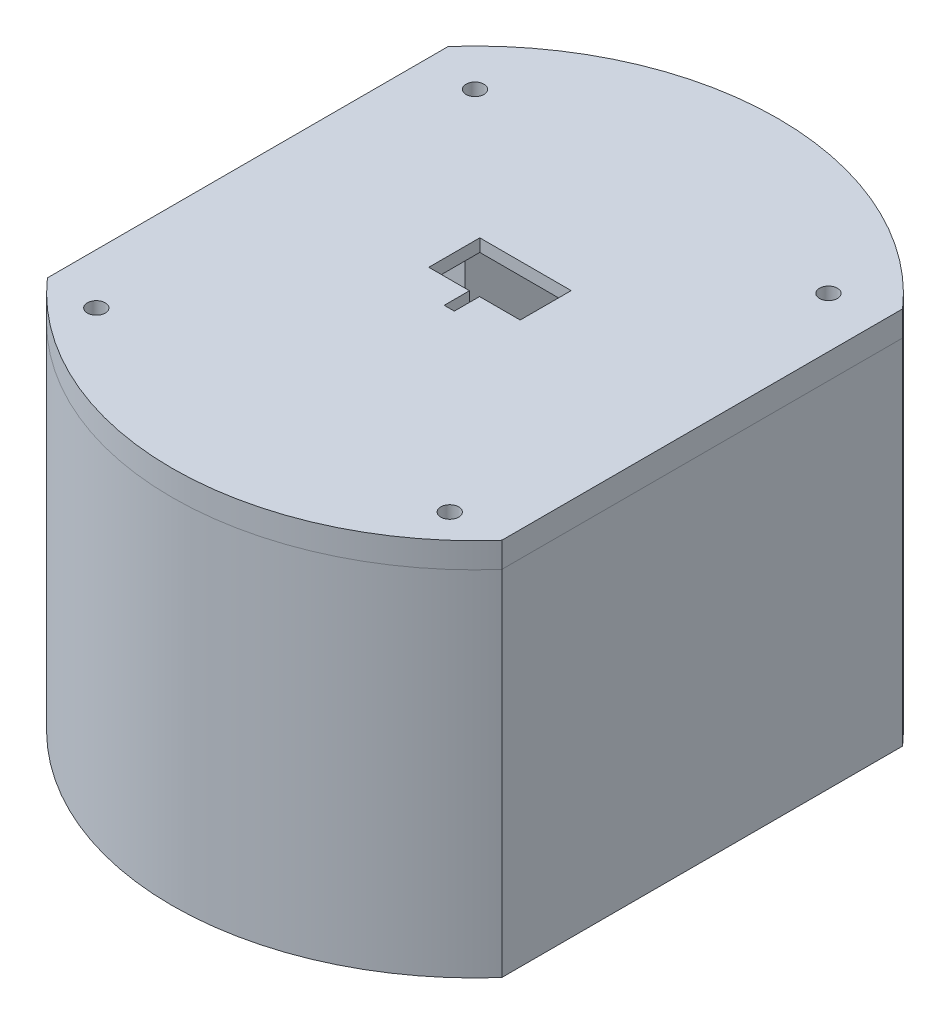
SolidWorks part; units mm, degrees
ref_plane "Front Plane" through (0, 0, 0) normal (0, 0, 1) x (1, 0, 0)
ref_plane "Top Plane" through (0, 0, 0) normal (0, 1, 0) x (1, 0, 0)
ref_plane "Right Plane" through (0, 0, 0) normal (1, 0, 0) x (0, 0, -1)
sketch "Sketch1" plane through (0, 0, 0) normal (0, 1, 0) x (1, 0, 0)
  circle A0 centre (0, 0) radius 76.2
  dimension "D1" = 152.4
extrude "Boss-Extrude1" add sketch "Sketch1" along normal blind 88.9
sketch "Sketch2" plane through (0, 88.9, 0) normal (0, 1, 0) x (1, 0, 0)
  line L2 (38.1, -58.5441) -> (38.1, 58.5441)
  line L4 (-38.1, -58.5441) -> (-38.1, 58.5441)
  arc A0 (38.1, 58.5441) -> (-38.1, 58.5441) centre (0, 0) ccw
  arc A1 (-38.1, -58.5441) -> (38.1, -58.5441) centre (0, 0) ccw
  dimension "D1" = 139.7
  dimension "D2" = 76.2
extrude "Cut-Extrude1" cut sketch "Sketch2" against normal blind 38.1
sketch "Sketch3" plane through (0, 0, 0) normal (0, -1, 0) x (1, 0, 0)
  line L0 (-40.64, 64.458) -> (-40.64, -64.458)
  line L1 (40.64, 64.458) -> (40.64, -64.458)
  line L2 (40.64, 23.1618) -> (-40.64, 23.1618)
  line L3 (40.64, -64.458) -> (-40.64, -64.458) construction
  circle A0 centre (0, 0) radius 76.2 construction
  arc A1 (-40.64, 64.458) -> (40.64, 64.458) centre (0, 0) cw
  arc A2 (-40.64, -64.458) -> (40.64, -64.458) centre (0, 0) ccw
  circle M5 centre (0, 0) radius 76.2
  dimension "D1" = 40.64
  dimension "D2" = 40.64
  dimension "D3" = 87.6197
extrude "Cut-Extrude2" cut sketch "Sketch3" against normal blind 71.12 contours L3 L1 L2 L0 | L3 M5
sketch "Sketch5" plane through (0, 88.9, 0) normal (0, 1, 0) x (1, 0, 0)
  line L2 (-57.15, 50.4016) -> (-57.15, -50.4016)
  line L4 (57.15, 50.4016) -> (57.15, -50.4016)
  circle A0 centre (0, 0) radius 76.2 construction
  arc A1 (-57.15, 50.4016) -> (-57.15, -50.4016) centre (0, 0) ccw
  arc A2 (57.15, -50.4016) -> (57.15, 50.4016) centre (0, 0) ccw
  dimension "D1" = 114.3
extrude "Cut-Extrude4" cut sketch "Sketch5" against normal through all
sketch "Sketch6" plane through (0, 88.9, 0) normal (0, 1, 0) x (1, 0, 0)
  line L0 (50.165, 38.1) -> (50.165, -44.45)
  line L1 (50.165, 38.1) -> (-50.165, 38.1)
  line L2 (50.165, -44.45) -> (-50.165, -44.45)
  line L3 (-50.165, 38.1) -> (-50.165, -44.45)
  arc A0 (38.1, 58.5441) -> (-38.1, 58.5441) centre (0, 0) ccw construction
  arc A1 (-38.1, -58.5441) -> (38.1, -58.5441) centre (0, 0) ccw construction
  point P7 (0, 69.85)
  point P8 (0, 38.1)
  point P13 (0, -69.85)
  dimension "D1" = 100.33
  dimension "D2" = 82.55
  dimension "D3" = 25.4
extrude "Cut-Extrude6" cut sketch "Sketch6" against normal up to surface (38.1 mm away) up to face at (0, 50.8, 43.6794)
sketch "Sketch7" plane through (0, 50.8, 0) normal (0, 1, 0) x (1, 0, 0)
  line L0 (40.64, 38.1) -> (50.165, 38.1)
  line L1 (40.64, 38.1) -> (40.64, 22.2769)
  line L2 (50.165, 38.1) -> (50.165, 22.2769)
  line L3 (40.64, 22.2769) -> (50.165, 22.2769)
extrude "Cut-Extrude7" cut sketch "Sketch7" against normal blind 13.716
hole_wizard "M4 Clearance Hole1" positions "Sketch9" profile "Sketch10" hole size "M4" standard "ANSI Metric"
sketch "Sketch9" plane through (0, 88.9, 0) normal (0, 1, 0) x (1, 0, 0)
  line L0 (-38.1, 58.5441) -> (-38.1, 38.1) construction
  line L1 (-38.1, 38.1) -> (-50.165, 38.1) construction
  line L2 (-38.1, -44.45) -> (-38.1, -58.5441) construction
  line L3 (-50.165, -44.45) -> (-38.1, -44.45) construction
  line L4 (38.1, -44.45) -> (50.165, -44.45) construction
  line L5 (38.1, -58.5441) -> (38.1, -44.45) construction
  line L6 (50.165, 38.1) -> (38.1, 38.1) construction
  line L7 (38.1, 38.1) -> (38.1, 58.5441) construction
  point P0 (44.45, 44.45)
  point P2 (-44.45, 44.45)
  point P4 (-44.45, -50.8)
  point P6 (44.45, -50.8)
  dimension "D1" = 6.35
  dimension "D2" = 6.35
  dimension "D3" = 6.35
  dimension "D4" = 6.35
  dimension "D5" = 6.35
  dimension "D6" = 6.35
  dimension "D7" = 6.35
  dimension "D8" = 6.35
sketch "Sketch10" plane through (44.45, 88.9, -44.45) normal (1, 0, 0) x (0, 0, 1)
  line L0 (0, 0) -> (0, 26.7519)
  line L1 (0, 26.7519) -> (2.25, 25.4)
  line L2 (2.25, 25.4) -> (2.25, 0)
  line L5 (2.25, 0) -> (0, 0)
  line L10 (0, 26.7519) -> (-2.25, 25.4) construction
  line L11 (0, -6.35) -> (0, 107.95) construction
  dimension "Hole Dia." = 4.5
  dimension "Hole Depth" = 25.4
  dimension "Drill Angle" = 118
sketch "Sketch11" plane through (0, 88.9, 0) normal (0, 1, 0) x (1, 0, 0)
  line L0 (-57.15, -50.4016) -> (-57.15, 50.4016) construction
  line L1 (57.15, 50.4016) -> (57.15, -50.4016) construction
  line L2 (-57.15, -50.4016) -> (-57.15, 50.4016)
  line L3 (57.15, 50.4016) -> (57.15, -50.4016)
  arc A0 (-57.15, -50.4016) -> (57.15, -50.4016) centre (0, 0) ccw construction
  arc A1 (57.15, 50.4016) -> (-57.15, 50.4016) centre (0, 0) ccw construction
  arc A2 (-57.15, -50.4016) -> (57.15, -50.4016) centre (0, 0) ccw
  arc A3 (57.15, 50.4016) -> (-57.15, 50.4016) centre (0, 0) ccw
  circle A4 centre (-44.45, -50.8) radius 2.25 construction
  circle A5 centre (-44.45, 44.45) radius 2.25 construction
  circle A6 centre (44.45, 44.45) radius 2.25 construction
  circle A7 centre (44.45, -50.8) radius 2.25 construction
  circle A8 centre (-44.45, -50.8) radius 2.25
  circle A9 centre (-44.45, 44.45) radius 2.25
  circle A10 centre (44.45, 44.45) radius 2.25
  circle A11 centre (44.45, -50.8) radius 2.25
extrude "Boss-Extrude2" add sketch "Sketch11" along normal blind 6.35 separate body
sketch "Sketch12" plane through (0, 95.25, 0) normal (0, 1, 0) x (1, 0, 0)
  line L10 (40.64, 64.458) -> (-40.64, 64.458) construction
  line L11 (-11.4935, 12.7) -> (-11.4935, -0.127)
  line L12 (-11.4935, 12.7) -> (11.4935, 12.7)
  line L13 (-11.4935, -0.127) -> (-1.27, -0.127)
  line L14 (11.4935, 12.7) -> (11.4935, -0.127)
  line L15 (-1.27, -0.127) -> (-1.27, -6.477)
  line L16 (-1.27, -6.477) -> (1.27, -6.477)
  line L17 (1.27, -0.127) -> (1.27, -6.477)
  line L18 (1.27, -0.127) -> (11.4935, -0.127)
  line L19 (50.165, 38.1) -> (-50.165, 38.1) construction
  point P0 (0, 12.7)
  point P3 (0, 64.458)
  dimension "D1" = 12.827
  dimension "D2" = 22.987
  dimension "D3" = 2.54
  dimension "D4" = 25.4
  dimension "D6" = 6.35
extrude "Cut-Extrude8" cut sketch "Sketch12" against normal blind 13.716
sketch "Sketch13" plane through (0, 88.9, 0) normal (0, -1, 0) x (1, 0, 0)
  line L0 (50.165, 44.45) -> (-50.165, 44.45) construction
  line L1 (-50.165, -38.1) -> (-50.165, 44.45) construction
  line L2 (50.165, -38.1) -> (50.165, 44.45) construction
  line L3 (50.165, -38.1) -> (-50.165, -38.1) construction
  line L4 (50.165, 44.45) -> (-50.165, 44.45)
  line L5 (-50.165, -38.1) -> (-50.165, 44.45)
  line L6 (50.165, -38.1) -> (50.165, 44.45)
  line L7 (50.165, -38.1) -> (-50.165, -38.1)
extrude "Cut-Extrude9" cut sketch "Sketch13" against normal blind 3.175
